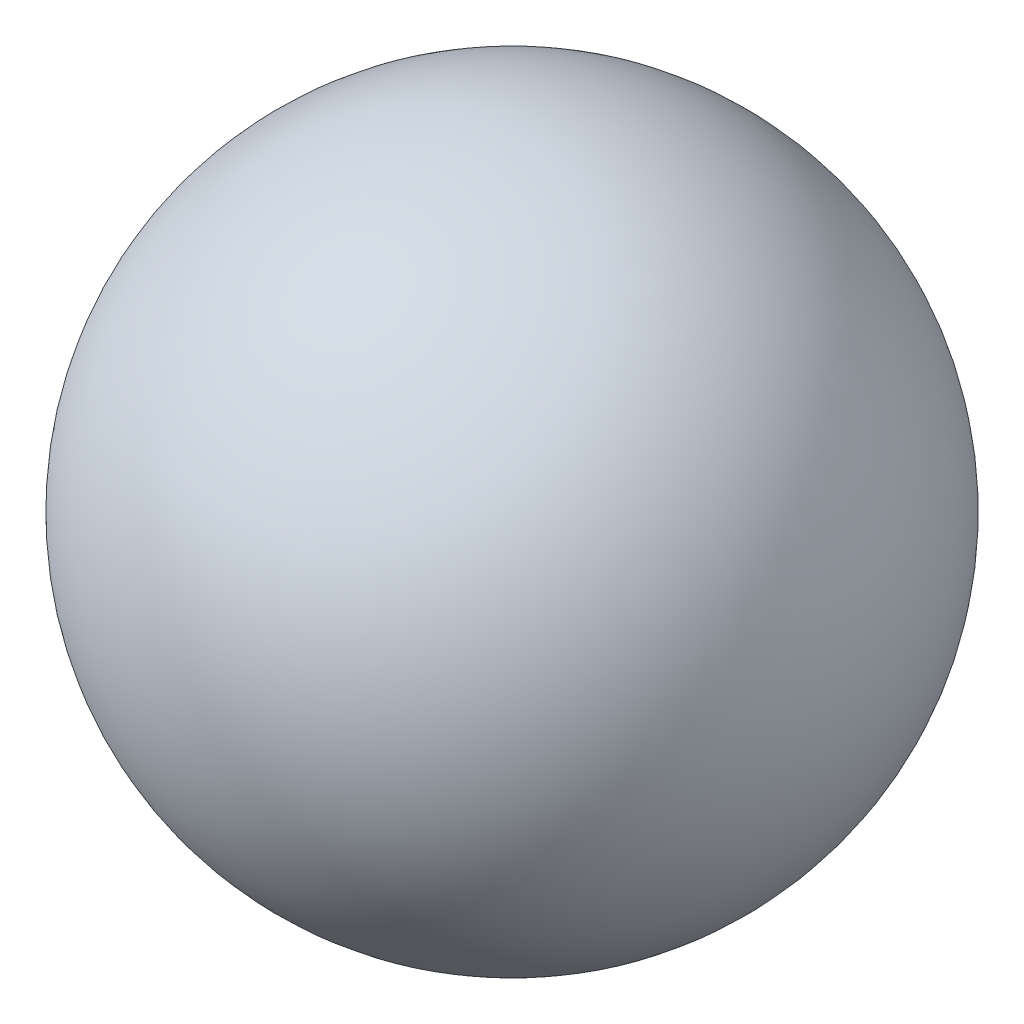
SolidWorks part; units mm, degrees
ref_plane "Front Plane" through (0, 0, 0) normal (0, 0, 1) x (1, 0, 0)
ref_plane "Top Plane" through (0, 0, 0) normal (0, 1, 0) x (1, 0, 0)
ref_plane "Right Plane" through (0, 0, 0) normal (1, 0, 0) x (0, 0, -1)
sketch "Sketch1" plane through (0, 0, 0) normal (0, 0, 1) x (1, 0, 0)
  line L0 (0, 3.452) -> (0, -3.8175) construction
  line L1 (0, 2.25) -> (0, -2.25)
  arc A0 (0, -2.25) -> (0, 2.25) centre (0, 0) ccw
  dimension "D1" = 4.5
revolve "Revolve4" add sketch "Sketch1" angle 360 about L0
